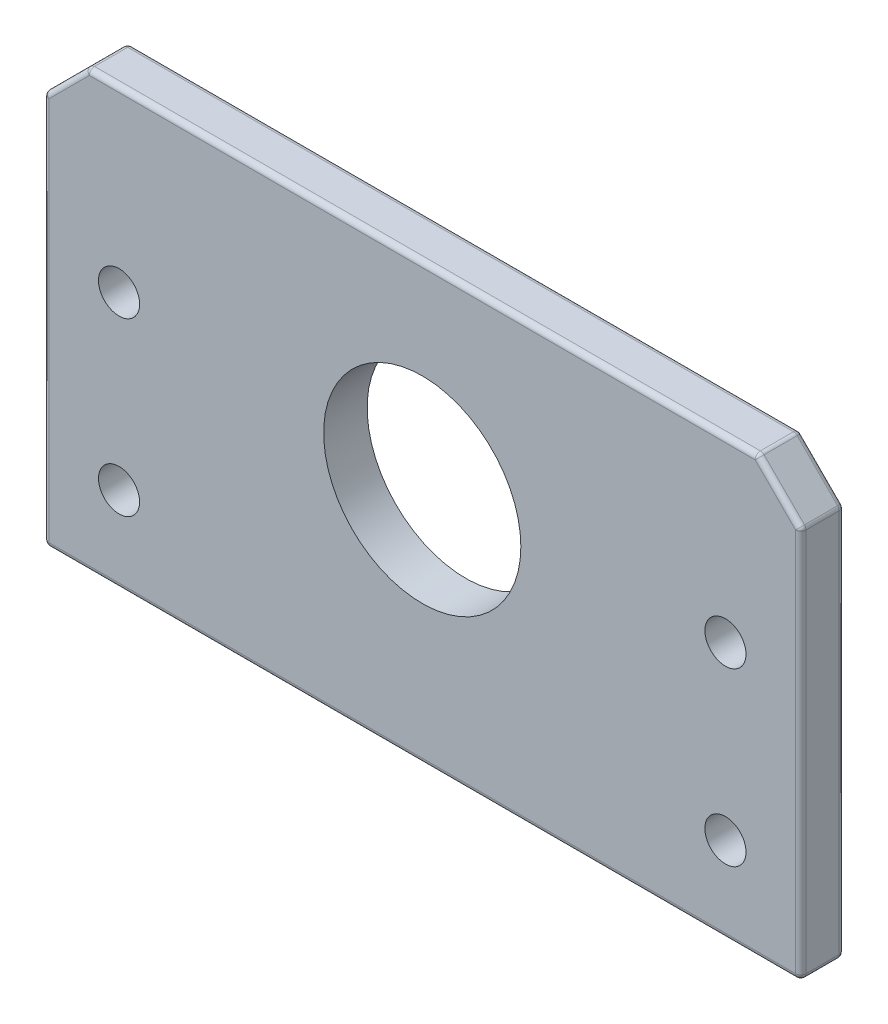
SolidWorks part; units mm, degrees
ref_plane "Front Plane" through (0, 0, 0) normal (0, 0, 1) x (1, 0, 0)
ref_plane "Top Plane" through (0, 0, 0) normal (0, 1, 0) x (1, 0, 0)
ref_plane "Right Plane" through (0, 0, 0) normal (1, 0, 0) x (0, 0, -1)
sketch "Sketch2" plane through (0, 0, 0) normal (0, 1, 0) x (1, 0, 0)
  line L1 (-55.245, 3.175) -> (55.245, 3.175)
  line L2 (-55.245, 3.175) -> (-55.245, -3.175)
  line L3 (-55.245, -3.175) -> (55.245, -3.175)
  line L4 (55.245, 3.175) -> (55.245, -3.175)
  point P4 (0, 3.175)
  point P7 (-55.245, 0)
  dimension "D1" = 6.35
  dimension "D2" = 110.49
extrude "Boss-Extrude1" add sketch "Sketch2" against normal blind 63.5
sketch "Sketch3" plane through (0, 0, 3.175) normal (0, 0, 1) x (1, 0, 0)
  line L2 (-55.245, 0) -> (55.245, 0) construction
  circle A0 centre (0, -28.815) radius 14.3891
  point P2 (0, 0)
  dimension "D1" = 28.815
  dimension "D3" = 28.7782
extrude "Cut-Extrude1" cut sketch "Sketch3" against normal through all
chamfer "Chamfer1" distance 6.35 angle 45 2 edges at (-55.245, 0, 0) (55.245, 0, 0)
fillet "Fillet1" [suppressed] radius 0.762
hole_wizard "CBORE for M4 SHCS2" [suppressed] positions "Sketch9" profile "Sketch10" counterbore size "M4" standard "ANSI Metric"
sketch "Sketch9" [suppressed] plane through (0, 0, 3.175) normal (0, 0, 1) x (1, 0, 0)
  line L0 (-48.5794, 0) -> (48.5794, 0) construction
  line L1 (-55.245, -62.738) -> (-55.245, -6.6656) construction
  point P0 (-17.9605, -10.8545)
  dimension "D1" = 10.8545
  dimension "D2" = 37.2845
sketch "Sketch10" plane through (-17.9605, -10.8545, 3.175) normal (1, 0, 0) x (0, -1, 0)
  line L0 (0, 0) -> (0, 6.35)
  line L1 (0, 6.35) -> (2.25, 6.35)
  line L3 (2.25, 6.35) -> (2.25, 4)
  line L4 (2.25, 4) -> (4, 4)
  line L5 (4, 4) -> (4, 0)
  line L7 (4, 0) -> (0, 0)
  line L11 (0, -6.35) -> (0, 107.95) construction
  dimension "Thru Hole Dia." = 4.5
  dimension "Thru Hole Depth" = 6.35
  dimension "C'Bore Dia." = 8
  dimension "C'Bore Depth" = 4
hole_wizard "Tap Drill for M7x1.0 Tap1" positions "Sketch17" profile "Sketch16" hole size "M7x1.0" standard "ANSI Metric" end condition through all
sketch "Sketch17" plane through (0, 0, -3.175) normal (0, 0, -1) x (-1, 0, 0)
  line L0 (0, 3.4925) -> (0, -3.4925) construction
  line L1 (-48.895, 0) -> (48.895, 0) construction
  point P0 (44.245, -26)
  point P3 (44.245, -51)
  point P6 (-44.245, -51)
  point P9 (-44.245, -26)
  dimension "D1" = 25
  dimension "D2" = 25
  dimension "D3" = 88.49
  dimension "D4" = 44.245
  dimension "D5" = 26
sketch "Sketch16" plane through (-44.245, -26, -3.175) normal (1, 0, 0) x (0, 1, 0)
  line L0 (0, 0) -> (0, 6.35)
  line L1 (0, 6.35) -> (3, 6.35)
  line L2 (3, 6.35) -> (3, 0)
  line L5 (3, 0) -> (0, 0)
  line L11 (0, -6.35) -> (0, 107.95) construction
  dimension "Thru Hole Dia." = 6
  dimension "Thru Hole Depth" = 6.35
fillet "Fillet2" radius 0.762 18 edges at (0, -63.5, 3.175) (0, -63.5, -3.175) (55.245, -63.5, 0) (55.245, -34.925, 3.175) (55.245, -34.925, -3.175) (52.07, -3.175, -3.175) (55.245, -6.35, 0) (52.07, -3.175, 3.175) (48.895, 0, 0) (0, 0, 3.175) (0, 0, -3.175) (-48.895, 0, 0) (-52.07, -3.175, 3.175) (-52.07, -3.175, -3.175) (-55.245, -63.5, 0) (-55.245, -34.925, -3.175) (-55.245, -6.35, 0) (-55.245, -34.925, 3.175)
